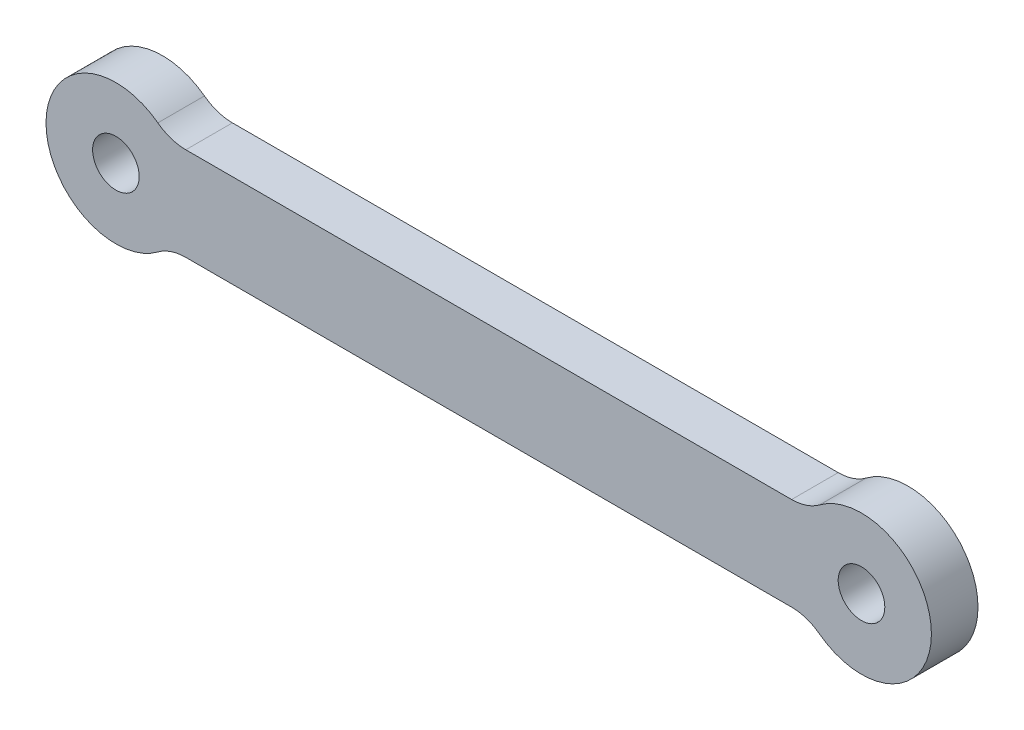
SolidWorks part; units mm, degrees
ref_plane "Front Plane" through (0, 0, 0) normal (0, 0, 1) x (1, 0, 0)
ref_plane "Top Plane" through (0, 0, 0) normal (0, 1, 0) x (1, 0, 0)
ref_plane "Right Plane" through (0, 0, 0) normal (1, 0, 0) x (0, 0, -1)
sketch "Sketch1" plane through (0, 0, 0) normal (0, 0, 1) x (1, 0, 0)
  line L0 (-101.6, 0) -> (0, 0) construction
  line L1 (-92.075, 6.35) -> (-9.525, 6.35)
  line L2 (-9.525, -6.35) -> (-92.075, -6.35)
  arc A0 (-5.715, -7.62) -> (-5.715, 7.62) centre (0, 0) ccw
  arc A1 (-95.885, 7.62) -> (-95.885, -7.62) centre (-101.6, 0) ccw
  arc A2 (-92.075, -6.35) -> (-95.885, -7.62) centre (-92.075, -12.7) ccw
  arc A3 (-9.525, -6.35) -> (-5.715, -7.62) centre (-9.525, -12.7) cw
  arc A4 (-9.525, 6.35) -> (-5.715, 7.62) centre (-9.525, 12.7) ccw
  arc A5 (-92.075, 6.35) -> (-95.885, 7.62) centre (-92.075, 12.7) cw
  circle A6 centre (-101.6, 0) radius 3.175
  circle A7 centre (0, 0) radius 3.175
  dimension "D1" = 19.05
  dimension "D4" = 6.35
  dimension "D5" = 6.35
  dimension "D2" = 101.6
  dimension "D3" = 12.7
extrude "Boss-Extrude1" add sketch "Sketch1" along normal mid plane 6.35
